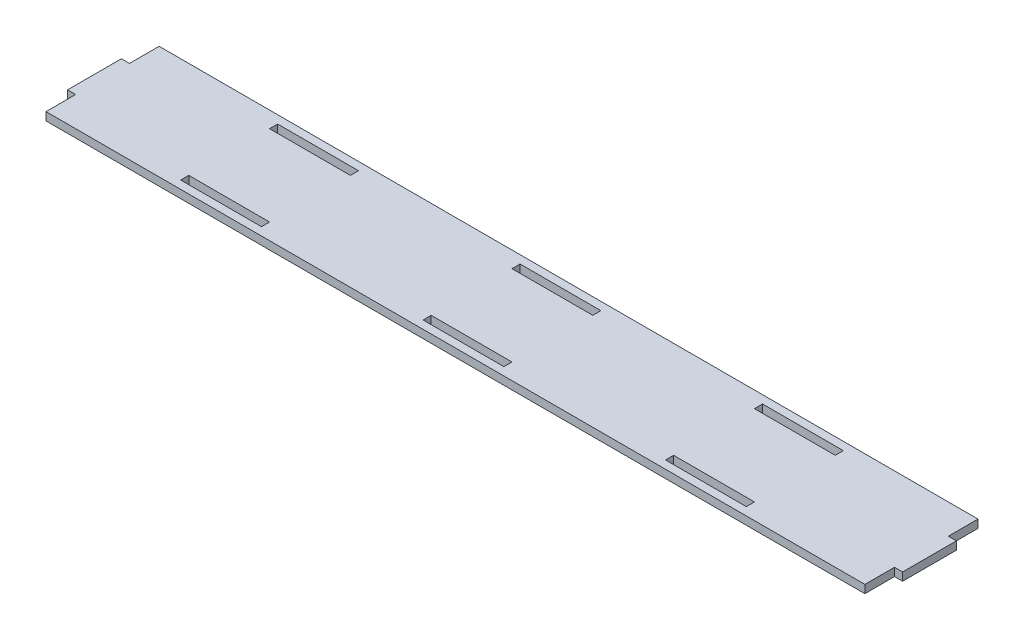
SolidWorks part; units mm, degrees
material "ABS"
ref_plane "Front Plane" through (0, 0, 0) normal (0, 0, 1) x (1, 0, 0)
ref_plane "Top Plane" through (0, 0, 0) normal (0, 1, 0) x (1, 0, 0)
ref_plane "Right Plane" through (0, 0, 0) normal (1, 0, 0) x (0, 0, -1)
sketch "Sketch1" plane through (0, 0, 0) normal (0, 1, 0) x (1, 0, 0)
  line L0 (-3, 21) -> (8.5953, 21) construction
  line L1 (0, 0) -> (304, 0)
  line L2 (0, 0) -> (0, 11)
  line L3 (0, 42) -> (304, 42)
  line L4 (304, 0) -> (304, 11)
  line L5 (0, 31) -> (-3, 31)
  line L7 (0, 11) -> (-3, 11)
  line L8 (-3, 31) -> (-3, 11)
  line L9 (304, 31) -> (307, 31)
  line L11 (304, 11) -> (307, 11)
  line L12 (307, 31) -> (307, 11)
  line L13 (47, 6) -> (77, 6)
  line L14 (47, 6) -> (47, 3)
  line L15 (47, 3) -> (77, 3)
  line L16 (77, 6) -> (77, 3)
  line L17 (137, 6) -> (167, 6)
  line L18 (137, 6) -> (137, 3)
  line L19 (137, 3) -> (167, 3)
  line L20 (167, 6) -> (167, 3)
  line L21 (227, 6) -> (257, 6)
  line L22 (227, 6) -> (227, 3)
  line L23 (227, 3) -> (257, 3)
  line L24 (257, 6) -> (257, 3)
  line L25 (257, 36) -> (257, 39)
  line L26 (227, 39) -> (257, 39)
  line L27 (227, 36) -> (227, 39)
  line L28 (227, 36) -> (257, 36)
  line L29 (167, 36) -> (167, 39)
  line L30 (137, 39) -> (167, 39)
  line L31 (137, 36) -> (137, 39)
  line L32 (137, 36) -> (167, 36)
  line L33 (77, 36) -> (77, 39)
  line L34 (47, 39) -> (77, 39)
  line L35 (47, 36) -> (47, 39)
  line L36 (47, 36) -> (77, 36)
  line L37 (304, 31) -> (304, 42)
  line L38 (0, 31) -> (0, 42)
  point P39 (0, 0)
  point P40 (-3, 21)
  dimension "D1" = 304
  dimension "D2" = 42
  dimension "D3" = 3
  dimension "D4" = 20
  dimension "D5" = 11
  dimension "D6" = 3
  dimension "D7" = 20
  dimension "D8" = 11
  dimension "D9" = 30
  dimension "D10" = 3
  dimension "D11" = 3
  dimension "D12" = 47
  dimension "D13" = 30
  dimension "D14" = 3
  dimension "D15" = 3
  dimension "D16" = 60
  dimension "D17" = 30
  dimension "D18" = 3
  dimension "D19" = 3
  dimension "D20" = 60
extrude "Boss-Extrude1" add sketch "Sketch1" along normal blind 3
